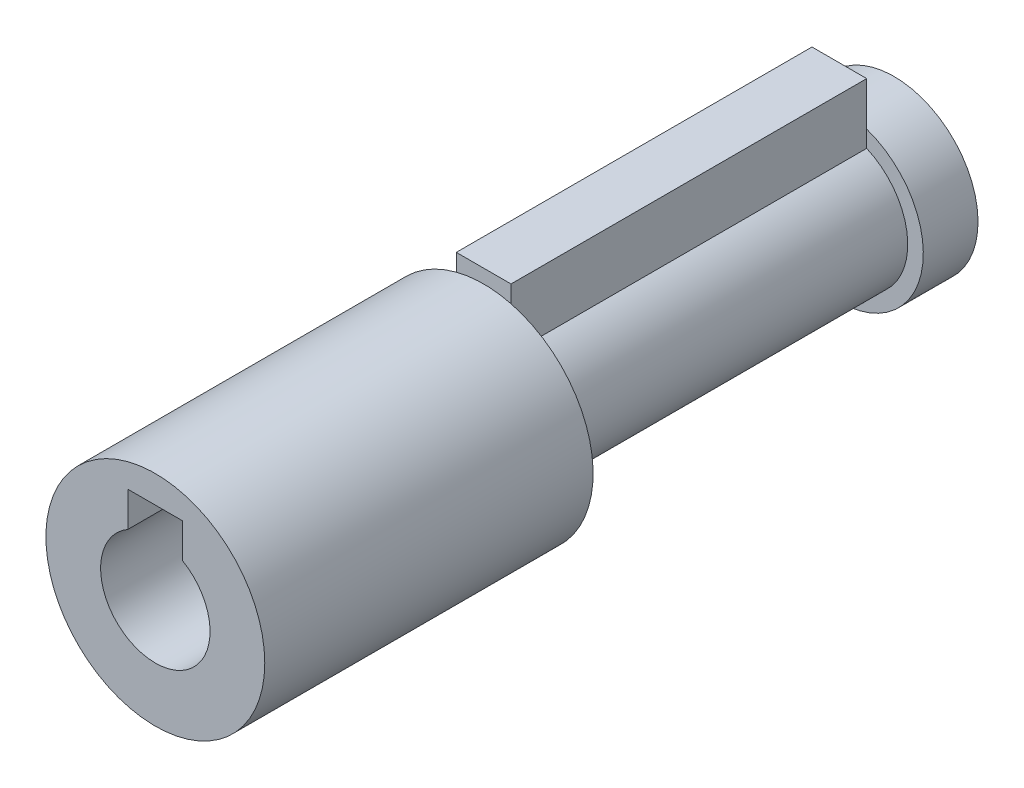
SolidWorks part; units mm, degrees
ref_plane "Front Plane" through (0, 0, 0) normal (0, 0, 1) x (1, 0, 0)
ref_plane "Top Plane" through (0, 0, 0) normal (0, 1, 0) x (1, 0, 0)
ref_plane "Right Plane" through (0, 0, 0) normal (1, 0, 0) x (0, 0, -1)
sketch "Sketch1" plane through (0, 0, 0) normal (0, 0, 1) x (1, 0, 0)
  line L1 (-1.27, 3.81) -> (1.27, 3.81)
  line L2 (-1.27, 3.81) -> (-1.27, 2.1997)
  line L4 (1.27, 3.81) -> (1.27, 2.1997)
  line L5 (-1.27, 3.81) -> (0, 2.54) construction
  line L6 (0, 2.54) -> (1.27, 3.81) construction
  circle A0 centre (0, 0) radius 2.54
  circle A1 centre (0, 0) radius 5.08
  point P4 (0, 2.54)
extrude "Boss-Extrude1" add sketch "Sketch1" along normal blind 12.7 contours A1 A0 L2 L1 L4
sketch "Sketch3" plane through (0, 0, 0) normal (0, 0, -1) x (-1, 0, 0)
  circle A0 centre (0, 0) radius 5.08
  circle A1 centre (0, 0) radius 5.08 construction
extrude "Boss-Extrude5" add sketch "Sketch3" along normal blind 2.54
sketch "Sketch5" plane through (0, 0, -2.54) normal (0, 0, -1) x (-1, 0, 0)
  line L1 (-1.27, 5.715) -> (1.27, 5.715)
  line L2 (-1.27, 5.715) -> (-1.27, 2.9099)
  line L4 (1.27, 5.715) -> (1.27, 2.9099)
  line L5 (-1.27, 5.715) -> (0, 3.175) construction
  line L6 (0, 3.175) -> (1.27, 5.715) construction
  arc A0 (-1.27, 2.9099) -> (1.27, 2.9099) centre (0, 0) ccw
  point P3 (0, 3.175)
extrude "Boss-Extrude7" add sketch "Sketch5" along normal blind 16.51
sketch "Sketch6" plane through (0, 0, -19.05) normal (0, 0, -1) x (-1, 0, 0)
  circle A0 centre (0, 0) radius 3.8971
extrude "Boss-Extrude8" add sketch "Sketch6" along normal blind 2.54
